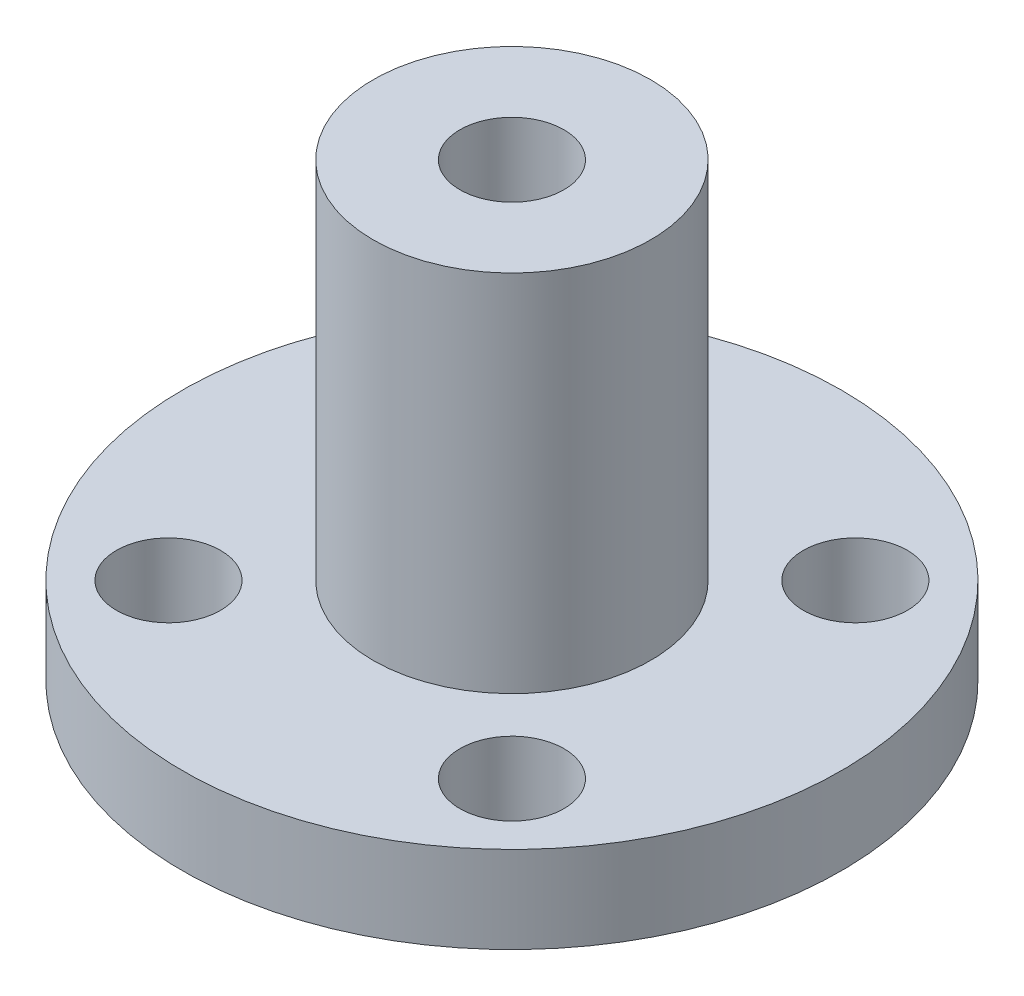
SolidWorks part; units mm, degrees
ref_plane "Front Plane" through (0, 0, 0) normal (0, 0, 1) x (1, 0, 0)
ref_plane "Top Plane" through (0, 0, 0) normal (0, 1, 0) x (1, 0, 0)
ref_plane "Right Plane" through (0, 0, 0) normal (1, 0, 0) x (0, 0, -1)
sketch "Sketch1" plane through (0, 0, 0) normal (0, 0, 1) x (1, 0, 0)
  line L0 (-1.5, -1.2241) -> (-9.5, -1.2241)
  line L1 (-9.5, -1.2241) -> (-9.5, 1.2759)
  line L2 (-9.5, 1.2759) -> (-4, 1.2759)
  line L3 (-4, 1.2759) -> (-4, 11.7759)
  line L4 (-4, 11.7759) -> (-1.5, 11.7759)
  line L6 (-1.5, 11.7759) -> (-1.5, -1.2241)
  line L7 (0, -0.9657) -> (0, 66.5021) construction
  point P0 (-48.4447, 1.2759)
  dimension "D1" = 13
  dimension "D2" = 8
  dimension "D3" = 8
  dimension "D4" = 2.5
  dimension "D5" = 1.5
revolve "Revolve1" add sketch "Sketch1" angle 360 about L7
sketch "Sketch2" plane through (0, -1.2241, 0) normal (0, -1, 0) x (1, 0, 0)
  line L0 (-4.9497, 4.9497) -> (0, 0) construction
  line L1 (0, 0) -> (-107.42, 0) construction
  circle A0 centre (-4.9497, 4.9497) radius 1.5
  circle A1 centre (4.9497, 4.9497) radius 1.5
  circle A2 centre (4.9497, -4.9497) radius 1.5
  circle A3 centre (-4.9497, -4.9497) radius 1.5
  point P14 (0, 0)
  dimension "D2" = 3
  dimension "D1" = 45
  dimension "D3" = 7
  dimension "D4" = 4
extrude "Cut-Extrude1" cut sketch "Sketch2" against normal blind 31
